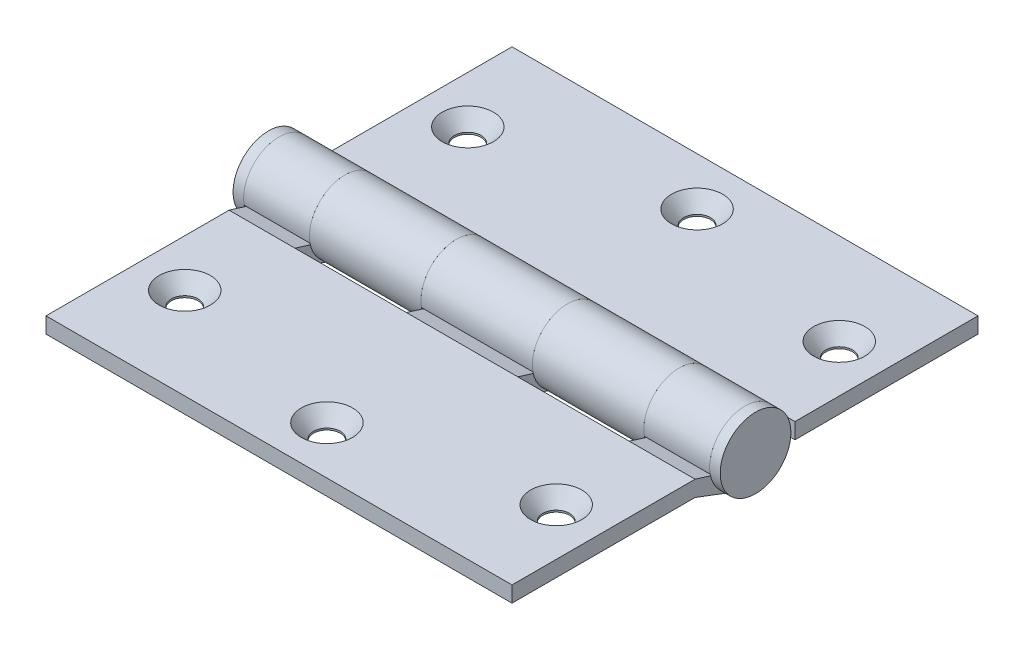
SolidWorks part; units mm, degrees
ref_plane "Front" through (0, 0, 0) normal (0, 0, 1) x (1, 0, 0)
ref_plane "Top" through (0, 0, 0) normal (0, 1, 0) x (1, 0, 0)
ref_plane "Right" through (0, 0, 0) normal (1, 0, 0) x (0, 0, -1)
sketch "Sketch1" plane through (0, 0, 0) normal (1, 0, 0) x (0, 0, -1)
  line L0 (-9.525, -3.6068) -> (-2.3899, -6.3094)
  line L1 (-44.45, -0.5842) -> (-9.525, -0.5842)
  line L2 (-9.525, -0.5842) -> (-0.9971, -3.2227)
  line L3 (-44.45, -3.6068) -> (-9.525, -3.6068)
  line L4 (-44.45, -0.5842) -> (-44.45, -3.6068)
  line L5 (-6.6372, -1.2118) -> (-2.1489, -2.6005)
  arc A0 (-0.9971, -3.2227) -> (-2.1489, -2.6005) centre (0, 0) ccw
  arc A1 (-2.3899, -6.3094) -> (-6.6372, -1.2118) centre (0, 0) ccw
  circle A2 centre (0, 0) radius 6.7469 construction
  circle A3 centre (0, 0) radius 3.3734 construction
  dimension "Pin Dia." = 6.7469
  dimension "Kn Dia" = 13.4937
  dimension "Th" = 3.0226
  dimension "D3" = 0.254
  dimension "Open Width / 2" = 44.45
  dimension "Leaf End" = 34.925
  dimension "Leaf Top" = 0.5842
extrude "Left Leaf" add sketch "Sketch1" along normal mid plane 88.9
sketch "Sketch2" plane through (0, 0, 0) normal (0, 1, 0) x (1, 0, 0)
  line L0 (31.8897, -9.525) -> (31.8897, 6.7469)
  line L2 (0, 6.7469) -> (0, -44.45) construction
  line L3 (44.45, 6.7469) -> (-44.45, 6.7469) construction
  line L4 (31.8897, 6.7469) -> (10.6299, 6.7469)
  line L5 (10.6299, 6.7469) -> (10.6299, -9.525)
  line L7 (44.45, -44.45) -> (-44.45, -44.45) construction
  line L8 (-31.8897, -9.525) -> (-31.8897, 6.7469)
  line L9 (10.6299, -9.525) -> (31.8897, -9.525)
  line L10 (-10.6299, -9.525) -> (-31.8897, -9.525)
  line L11 (-10.6299, 6.7469) -> (-10.6299, -9.525)
  line L12 (-31.8897, 6.7469) -> (-10.6299, 6.7469)
  line L14 (-10.6299, 6.7469) -> (10.6299, 6.7469) construction
  dimension "Knuckle Lg" = 21.2598
extrude "Cut-Extrude1" cut sketch "Sketch2" against normal through all and the other way through all
sketch "Sketch3" plane through (31.8897, 0, 0) normal (1, 0, 0) x (0, 0, -1)
  line L0 (0, 6.7469) -> (0, -3.6068) construction
  line L1 (-44.45, -3.6068) -> (-9.525, -3.6068) construction
  line L2 (9.525, -3.6068) -> (2.3899, -6.3094)
  line L3 (9.525, -0.5842) -> (0.9971, -3.2227)
  line L4 (2.1489, -2.6005) -> (6.6372, -1.2118)
  line L6 (9.525, -3.6068) -> (44.45, -3.6068)
  line L7 (44.45, -3.6068) -> (44.45, -0.5842)
  line L9 (-44.45, -0.5842) -> (-44.45, -3.6068) construction
  line L10 (44.45, -0.5842) -> (9.525, -0.5842)
  arc A0 (-2.3899, -6.3094) -> (-6.6372, -1.2118) centre (0, 0) ccw construction
  circle A5 centre (0, 0) radius 6.7469 construction
  arc A6 (2.3899, -6.3094) -> (6.6372, -1.2118) centre (0, 0) cw
  arc A7 (-0.9971, -3.2227) -> (-2.1489, -2.6005) centre (0, 0) ccw construction
  arc A8 (2.1489, -2.6005) -> (0.9971, -3.2227) centre (0, 0) ccw
extrude "Right Leaf" add sketch "Sketch3" against normal up to surface (21.2598 mm away) separate body up to face at (10.6299, -0.5961, 3.0583)
mirror "Mirror1" about plane through (0, 0, 0) normal (1, 0, 0) of bodies 110
sketch "Sketch4" plane through (0, 0, 0) normal (-1, 0, 0) x (0, 0, 1)
  line L0 (-9.525, -0.5842) -> (-9.525, -3.6068)
  line L1 (-44.45, -0.5842) -> (-9.525, -0.5842)
  line L2 (0, 6.7469) -> (0, -3.6068) construction
  line L6 (-9.525, -3.6068) -> (-44.45, -3.6068)
  line L8 (-44.45, -3.6068) -> (-44.45, -0.5842)
extrude "Extrude3" add sketch "Sketch4" along normal up to surface and the other way up to surface
combine bodies "Combine1" operation type add bodies to combine 125 110 111
sketch "Sketch6" plane through (0, 0, 0) normal (0, 1, 0) x (1, 0, 0)
  line L0 (24.5662, 0) -> (-23.3403, 0) construction
  line L1 (44.45, -6.7469) -> (44.45, 6.7469) construction
  line L2 (-44.45, 0) -> (44.45, 0)
  line L3 (-44.45, 0) -> (-44.45, -3.3734)
  line L4 (-44.45, -3.3734) -> (44.45, -3.3734)
  line L5 (44.45, 0) -> (44.45, -3.3734)
  line L6 (-44.45, -3.3734) -> (-44.45, 3.3734) construction
  dimension "D1" = 6.7469
revolve "Pin" add sketch "Sketch6" angle 360 about L0
sketch "Sketch7" plane through (0, 0, 0) normal (0, 1, 0) x (1, 0, 0)
  line L0 (24.5662, 0) -> (-23.3403, 0) construction
  line L1 (0, 44.45) -> (0, -44.45) construction
  line L2 (24.5662, 0) -> (-23.3403, 0) construction
  line L3 (-46.4651, 0) -> (-46.4651, -6.7469)
  line L4 (-46.4651, 0) -> (-44.45, 0)
  line L5 (-44.45, 0) -> (-44.45, -6.7469)
  line L6 (-44.45, 44.45) -> (44.45, 44.45) construction
  line L7 (-46.4651, -6.7469) -> (-44.45, -6.7469)
  line L8 (46.4651, 0) -> (46.4651, -6.7469)
  line L9 (44.45, 0) -> (44.45, -6.7469)
  line L10 (46.4651, 0) -> (44.45, 0)
  line L11 (46.4651, -6.7469) -> (44.45, -6.7469)
  dimension "D1" = 2.0151
revolve "Spun Pin" add sketch "Sketch7" angle 360 about L0
sketch "Sketch8" plane through (0, -0.5842, 0) normal (0, 1, 0) x (-1, 0, 0)
  line L0 (-44.45, -44.45) -> (44.45, -44.45) construction
  line L3 (44.45, 0) -> (-44.45, 0) construction
  line L4 (0, -44.45) -> (0, 44.45) construction
  line L5 (44.45, -44.45) -> (-44.45, -44.45) construction
  line L6 (0, 44.45) -> (0, 9.525) construction
  line L7 (-44.45, 44.45) -> (44.45, 44.45) construction
  point P3 (35.433, -27.0002)
  point P4 (-35.433, -27.0002)
  point P8 (-35.433, 27.0002)
  point P9 (35.433, 27.0002)
  point P26 (0, -35.306)
  point P27 (0, 35.306)
  dimension "D1" = 17.4498
  dimension "Hole Dist" = 35.433
  dimension "Hole Dist3" = 9.144
hole_wizard "CSK for #10 Flat Head Machine Screw1" positions "3DSketch1" profile "Sketch9" countersink size "#10" standard "Ansi Inch" end condition through all
sketch3d "3DSketch1"
  point P30 (-35.433, -0.5842, 27.0002)
  point P33 (-35.433, -0.5842, -27.0002)
  point P36 (35.433, -0.5842, -27.0002)
  point P39 (35.433, -0.5842, 27.0002)
  point P56 (0, -0.5842, -35.306)
  point P59 (0, -0.5842, 35.306)
sketch "Sketch9" plane through (-35.433, -0.5842, 27.0002) normal (1, 0, 0) x (0, 0, 1)
  line L0 (0, 0) -> (0, 6.1627)
  line L1 (0, 6.1627) -> (2.5527, 6.1627)
  line L2 (2.5527, 6.1627) -> (2.5527, 2.6882)
  line L3 (2.5527, 2.6882) -> (4.8895, 0)
  line L5 (4.8895, 0) -> (0, 0)
  line L6 (-2.5527, 2.6882) -> (-4.8895, 0) construction
  line L11 (0, -6.35) -> (0, 107.95) construction
  dimension "Thru Hole Dia." = 5.1054
  dimension "Thru Hole Depth" = 6.1627
  dimension "Near C'Sink Dia." = 9.779
  dimension "Near C'Sink Angle" = 82
equation "\"D1@Sketch7\"=\"Th@Sketch1\"/1.5"
equation "\"D1@Sketch6\" = \"Pin Dia.@Sketch1\""
